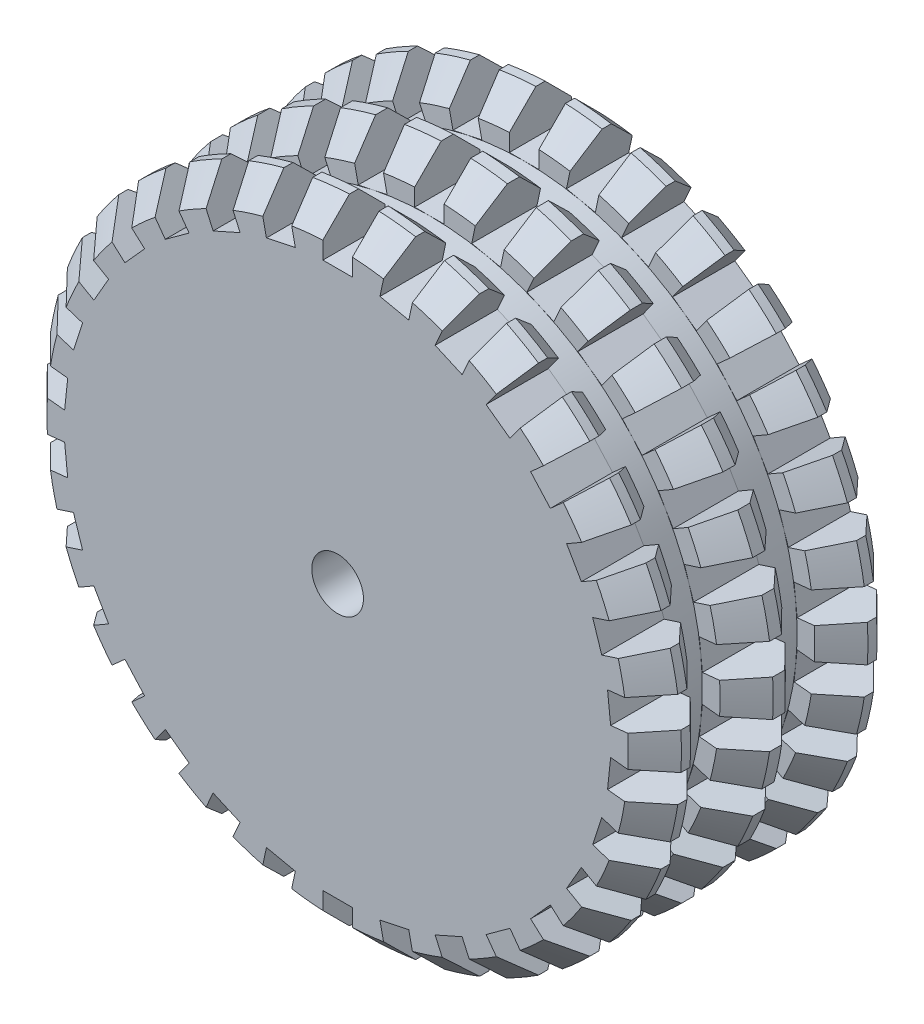
SolidWorks part; units mm, degrees
material "PET"
ref_plane "Alzado" through (0, 0, 0) normal (0, 0, 1) x (1, 0, 0)
ref_plane "Planta" through (0, 0, 0) normal (0, 1, 0) x (1, 0, 0)
ref_plane "Vista lateral" through (0, 0, 0) normal (1, 0, 0) x (0, 0, -1)
sketch "Sketch1" plane through (0, 0, 0) normal (0, 0, 1) x (1, 0, 0)
  circle A0 centre (0, 0) radius 21.5
  circle A1 centre (0, 0) radius 1.75
  dimension "D1" = 43
  dimension "D2" = 3.5
extrude "Boss-Extrude1" add sketch "Sketch1" along normal blind 16.86
sketch "Croquis1" plane through (0, 0, 16.86) normal (0, 0, 1) x (1, 0, 0)
  line L0 (0, 0) -> (0, 21.5) construction
  line L2 (-1, 22.5) -> (1, 22.5)
  line L3 (-1, 22.5) -> (-1, 18.5)
  line L4 (-1, 18.5) -> (1, 18.5)
  line L5 (1, 22.5) -> (1, 18.5)
  circle A0 centre (0, 0) radius 21.5 construction
  point P10 (0, 22.5)
  dimension "D1" = 3
  dimension "D2" = 1
  dimension "D3" = 2
extrude "Cortar-Extruir1" cut sketch "Croquis1" against normal through all
ref_plane "Plano1" through (0, 0, 11.64) normal (0, 0, 1) x (1, 0, 0)
sketch "Croquis2" plane through (0, 0, 11.64) normal (0, 0, 1) x (1, 0, 0)
  line L0 (-1, 18.5) -> (1, 18.5) construction
  circle A0 centre (0, 0) radius 18.5
  circle A1 centre (0, 0) radius 21.5
extrude "Cortar-Extruir2" cut sketch "Croquis2" against normal mid plane 2
ref_plane "Plano2" through (0, 0, 5.22) normal (0, 0, -1) x (-1, 0, 0)
sketch "Croquis3" plane through (0, 0, 5.22) normal (0, 0, -1) x (-1, 0, 0)
  line L0 (1, 18.5) -> (-1, 18.5) construction
  circle A0 centre (0, 0) radius 18.5
  circle A1 centre (0, 0) radius 21.5
extrude "Cortar-Extruir3" cut sketch "Croquis3" against normal mid plane 2
chamfer "Chaflán1" distance 1.8 angle 45 6 edges at (0, -21.5, 16.86) (0, -21.5, 12.64) (0, -21.5, 4.22) (0, -21.5, 0) (0, -21.5, 6.22) (0, -21.5, 10.64)
pattern_circular "MatrizC1" count 30 over 360 about axis through (0, 0, 0) along (0, 0, 1) of "Cortar-Extruir1"
